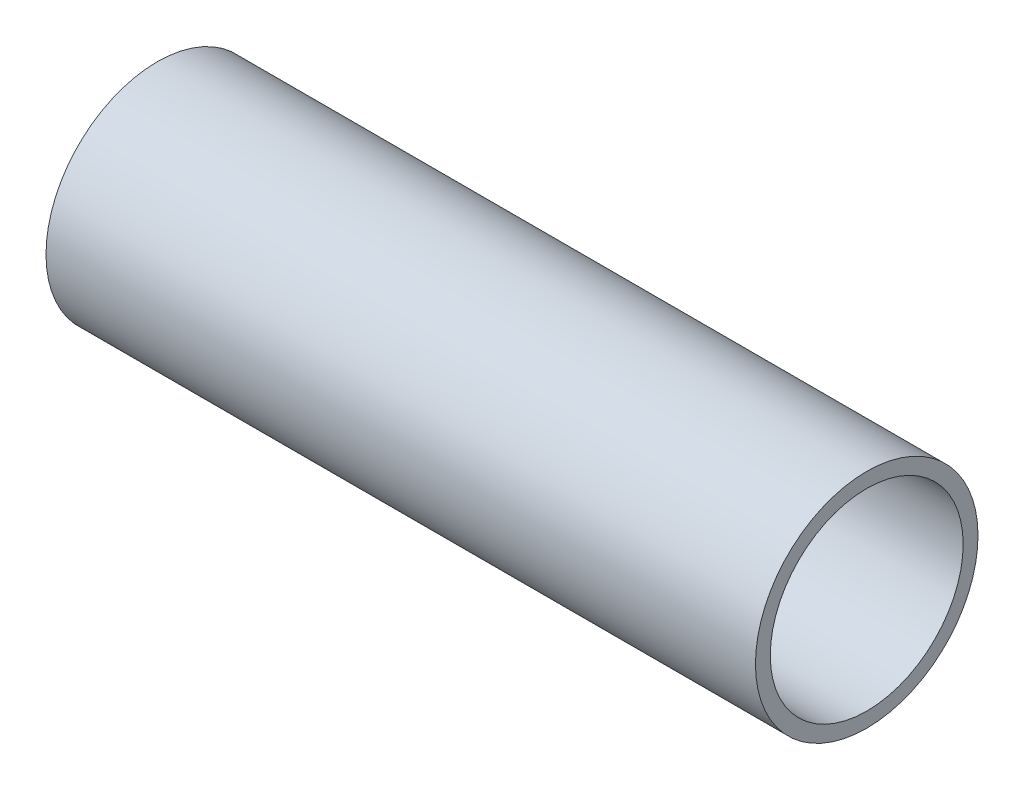
SolidWorks part; units mm, degrees
ref_plane "前视基准面" through (0, 0, 0) normal (0, 0, 1) x (1, 0, 0)
ref_plane "上视基准面" through (0, 0, 0) normal (0, 1, 0) x (1, 0, 0)
ref_plane "右视基准面" through (0, 0, 0) normal (1, 0, 0) x (0, 0, -1)
sketch "草图1" plane through (0, 0, 0) normal (1, 0, 0) x (0, 0, -1)
  circle A0 centre (0, 0) radius 7.5
  circle A1 centre (0, 0) radius 6.5
  dimension "D1" = 15
  dimension "D2" = 13
extrude "凸台-拉伸1" add sketch "草图1" along normal blind 47.82
